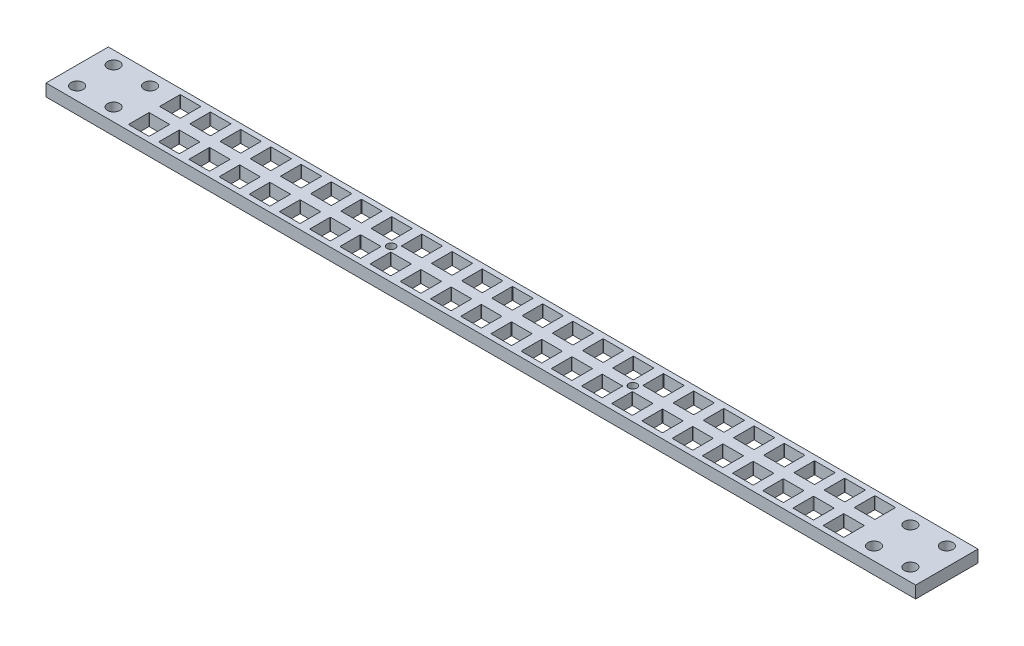
SolidWorks part; units mm, degrees
ref_plane "Front Plane" through (0, 0, 0) normal (0, 0, 1) x (1, 0, 0)
ref_plane "Top Plane" through (0, 0, 0) normal (0, 1, 0) x (1, 0, 0)
ref_plane "Right Plane" through (0, 0, 0) normal (1, 0, 0) x (0, 0, -1)
sketch "Sketch3" plane through (0, 0, 0) normal (0, 1, 0) x (1, 0, 0)
  line L0 (-49.8596, 35.1681) -> (-44.9596, 35.1681)
  line L1 (-57.4196, 42.8681) -> (119.2604, 42.8681) construction
  line L2 (-57.4196, 42.8681) -> (-57.4196, 30.0681) construction
  line L3 (-57.4196, 30.0681) -> (119.2604, 30.0681) construction
  line L4 (119.2604, 42.8681) -> (119.2604, 30.0681) construction
  line L5 (-57.4196, 42.8681) -> (119.2604, 30.0681) construction
  line L6 (-54.8696, 35.6681) -> (-54.8696, 32.6181) construction
  line L7 (-57.4196, 30.0681) -> (119.2604, 42.8681) construction
  line L8 (-57.2946, 35.0431) -> (-52.4446, 35.0431) construction
  line L9 (-57.2946, 35.0431) -> (-57.2946, 30.1931) construction
  line L10 (-57.2946, 30.1931) -> (-52.4446, 30.1931) construction
  line L11 (-52.4446, 35.0431) -> (-52.4446, 30.1931) construction
  line L12 (-57.2946, 35.0431) -> (-52.4446, 30.1931) construction
  line L13 (-57.2946, 30.1931) -> (-52.4446, 35.0431) construction
  line L14 (-57.3196, 35.1681) -> (-52.4196, 35.1681)
  line L15 (-57.4196, 35.0681) -> (-57.4196, 30.1681)
  line L16 (-57.3196, 30.0681) -> (-52.4196, 30.0681)
  line L17 (-52.3196, 35.0681) -> (-52.3196, 30.1681)
  line L18 (-57.4196, 35.1681) -> (-52.3196, 30.0681) construction
  line L19 (-57.4196, 30.0681) -> (-52.3196, 35.1681) construction
  line L20 (-49.9596, 35.0681) -> (-49.9596, 30.1681)
  line L21 (-49.8596, 30.0681) -> (-44.9596, 30.0681)
  line L22 (-44.8596, 35.0681) -> (-44.8596, 30.1681)
  line L24 (-47.4096, 35.6681) -> (-47.4096, 32.6181) construction
  line L25 (-49.8346, 35.0431) -> (-44.9846, 35.0431) construction
  line L26 (-49.8346, 35.0431) -> (-49.8346, 30.1931) construction
  line L27 (-49.8346, 30.1931) -> (-44.9846, 30.1931) construction
  line L28 (-44.9846, 35.0431) -> (-44.9846, 30.1931) construction
  line L29 (-49.8346, 35.0431) -> (-44.9846, 30.1931) construction
  line L30 (-49.8346, 30.1931) -> (-44.9846, 35.0431) construction
  line L31 (-49.9596, 35.1681) -> (-44.8596, 30.0681) construction
  line L32 (-49.9596, 30.0681) -> (-44.8596, 35.1681) construction
  line L33 (-42.3996, 35.1681) -> (-37.4996, 35.1681)
  line L34 (-42.4996, 35.0681) -> (-42.4996, 30.1681)
  line L35 (-42.3996, 30.0681) -> (-37.4996, 30.0681)
  line L36 (-37.3996, 35.0681) -> (-37.3996, 30.1681)
  line L37 (-76.4776, 44.1681) -> (138.3183, 44.1681)
  line L38 (-39.9496, 35.6681) -> (-39.9496, 32.6181) construction
  line L39 (-42.3746, 35.0431) -> (-37.5246, 35.0431) construction
  line L40 (-42.3746, 35.0431) -> (-42.3746, 30.1931) construction
  line L41 (-42.3746, 30.1931) -> (-37.5246, 30.1931) construction
  line L42 (-37.5246, 35.0431) -> (-37.5246, 30.1931) construction
  line L43 (-42.3746, 35.0431) -> (-37.5246, 30.1931) construction
  line L44 (-42.3746, 30.1931) -> (-37.5246, 35.0431) construction
  line L45 (-42.4996, 35.1681) -> (-37.3996, 30.0681) construction
  line L46 (-42.4996, 30.0681) -> (-37.3996, 35.1681) construction
  line L47 (-34.9396, 35.1681) -> (-30.0396, 35.1681)
  line L48 (-35.0396, 35.0681) -> (-35.0396, 30.1681)
  line L49 (-34.9396, 30.0681) -> (-30.0396, 30.0681)
  line L50 (-29.9396, 35.0681) -> (-29.9396, 30.1681)
  line L51 (-76.4776, 44.1681) -> (-76.4776, 28.7681)
  line L52 (-32.4896, 35.6681) -> (-32.4896, 32.6181) construction
  line L53 (-34.9146, 35.0431) -> (-30.0646, 35.0431) construction
  line L54 (-34.9146, 35.0431) -> (-34.9146, 30.1931) construction
  line L55 (-34.9146, 30.1931) -> (-30.0646, 30.1931) construction
  line L56 (-30.0646, 35.0431) -> (-30.0646, 30.1931) construction
  line L57 (-34.9146, 35.0431) -> (-30.0646, 30.1931) construction
  line L58 (-34.9146, 30.1931) -> (-30.0646, 35.0431) construction
  line L59 (-35.0396, 35.1681) -> (-29.9396, 30.0681) construction
  line L60 (-35.0396, 30.0681) -> (-29.9396, 35.1681) construction
  line L61 (-27.4796, 35.1681) -> (-22.5796, 35.1681)
  line L62 (-27.5796, 35.0681) -> (-27.5796, 30.1681)
  line L63 (-27.4796, 30.0681) -> (-22.5796, 30.0681)
  line L64 (-22.4796, 35.0681) -> (-22.4796, 30.1681)
  line L65 (-76.4776, 28.7681) -> (138.3183, 28.7681)
  line L66 (-25.0296, 35.6681) -> (-25.0296, 32.6181) construction
  line L67 (-27.4546, 35.0431) -> (-22.6046, 35.0431) construction
  line L68 (-27.4546, 35.0431) -> (-27.4546, 30.1931) construction
  line L69 (-27.4546, 30.1931) -> (-22.6046, 30.1931) construction
  line L70 (-22.6046, 35.0431) -> (-22.6046, 30.1931) construction
  line L71 (-27.4546, 35.0431) -> (-22.6046, 30.1931) construction
  line L72 (-27.4546, 30.1931) -> (-22.6046, 35.0431) construction
  line L73 (-27.5796, 35.1681) -> (-22.4796, 30.0681) construction
  line L74 (-27.5796, 30.0681) -> (-22.4796, 35.1681) construction
  line L75 (-20.0196, 35.1681) -> (-15.1196, 35.1681)
  line L76 (-20.1196, 35.0681) -> (-20.1196, 30.1681)
  line L77 (-20.0196, 30.0681) -> (-15.1196, 30.0681)
  line L78 (-15.0196, 35.0681) -> (-15.0196, 30.1681)
  line L79 (138.3183, 44.1681) -> (138.3183, 28.7681)
  line L80 (-17.5696, 35.6681) -> (-17.5696, 32.6181) construction
  line L81 (-19.9946, 35.0431) -> (-15.1446, 35.0431) construction
  line L82 (-19.9946, 35.0431) -> (-19.9946, 30.1931) construction
  line L83 (-19.9946, 30.1931) -> (-15.1446, 30.1931) construction
  line L84 (-15.1446, 35.0431) -> (-15.1446, 30.1931) construction
  line L85 (-19.9946, 35.0431) -> (-15.1446, 30.1931) construction
  line L86 (-19.9946, 30.1931) -> (-15.1446, 35.0431) construction
  line L87 (-20.1196, 35.1681) -> (-15.0196, 30.0681) construction
  line L88 (-20.1196, 30.0681) -> (-15.0196, 35.1681) construction
  line L89 (-12.5596, 35.1681) -> (-7.6596, 35.1681)
  line L90 (-12.6596, 35.0681) -> (-12.6596, 30.1681)
  line L91 (-12.5596, 30.0681) -> (-7.6596, 30.0681)
  line L92 (-7.5596, 35.0681) -> (-7.5596, 30.1681)
  line L93 (-76.4776, 44.1681) -> (138.3183, 28.7681) construction
  line L94 (-10.1096, 35.6681) -> (-10.1096, 32.6181) construction
  line L95 (-12.5346, 35.0431) -> (-7.6846, 35.0431) construction
  line L96 (-12.5346, 35.0431) -> (-12.5346, 30.1931) construction
  line L97 (-12.5346, 30.1931) -> (-7.6846, 30.1931) construction
  line L98 (-7.6846, 35.0431) -> (-7.6846, 30.1931) construction
  line L99 (-12.5346, 35.0431) -> (-7.6846, 30.1931) construction
  line L100 (-12.5346, 30.1931) -> (-7.6846, 35.0431) construction
  line L101 (-12.6596, 35.1681) -> (-7.5596, 30.0681) construction
  line L102 (-12.6596, 30.0681) -> (-7.5596, 35.1681) construction
  line L103 (-5.0996, 35.1681) -> (-0.1996, 35.1681)
  line L104 (-5.1996, 35.0681) -> (-5.1996, 30.1681)
  line L105 (-5.0996, 30.0681) -> (-0.1996, 30.0681)
  line L106 (-0.0996, 35.0681) -> (-0.0996, 30.1681)
  line L107 (-76.4776, 28.7681) -> (138.3183, 44.1681) construction
  line L108 (-2.6496, 35.6681) -> (-2.6496, 32.6181) construction
  line L109 (-5.0746, 35.0431) -> (-0.2246, 35.0431) construction
  line L110 (-5.0746, 35.0431) -> (-5.0746, 30.1931) construction
  line L111 (-5.0746, 30.1931) -> (-0.2246, 30.1931) construction
  line L112 (-0.2246, 35.0431) -> (-0.2246, 30.1931) construction
  line L113 (-5.0746, 35.0431) -> (-0.2246, 30.1931) construction
  line L114 (-5.0746, 30.1931) -> (-0.2246, 35.0431) construction
  line L115 (-5.1996, 35.1681) -> (-0.0996, 30.0681) construction
  line L116 (-5.1996, 30.0681) -> (-0.0996, 35.1681) construction
  line L117 (2.3604, 35.1681) -> (7.2604, 35.1681)
  line L118 (2.2604, 35.0681) -> (2.2604, 30.1681)
  line L119 (2.3604, 30.0681) -> (7.2604, 30.0681)
  line L120 (7.3604, 35.0681) -> (7.3604, 30.1681)
  line L122 (4.8104, 35.6681) -> (4.8104, 32.6181) construction
  line L123 (2.3854, 35.0431) -> (7.2354, 35.0431) construction
  line L124 (2.3854, 35.0431) -> (2.3854, 30.1931) construction
  line L125 (2.3854, 30.1931) -> (7.2354, 30.1931) construction
  line L126 (7.2354, 35.0431) -> (7.2354, 30.1931) construction
  line L127 (2.3854, 35.0431) -> (7.2354, 30.1931) construction
  line L128 (2.3854, 30.1931) -> (7.2354, 35.0431) construction
  line L129 (2.2604, 35.1681) -> (7.3604, 30.0681) construction
  line L130 (2.2604, 30.0681) -> (7.3604, 35.1681) construction
  line L131 (9.8204, 35.1681) -> (14.7204, 35.1681)
  line L132 (9.7204, 35.0681) -> (9.7204, 30.1681)
  line L133 (9.8204, 30.0681) -> (14.7204, 30.0681)
  line L134 (14.8204, 35.0681) -> (14.8204, 30.1681)
  line L136 (12.2704, 35.6681) -> (12.2704, 32.6181) construction
  line L137 (9.8454, 35.0431) -> (14.6954, 35.0431) construction
  line L138 (9.8454, 35.0431) -> (9.8454, 30.1931) construction
  line L139 (9.8454, 30.1931) -> (14.6954, 30.1931) construction
  line L140 (14.6954, 35.0431) -> (14.6954, 30.1931) construction
  line L141 (9.8454, 35.0431) -> (14.6954, 30.1931) construction
  line L142 (9.8454, 30.1931) -> (14.6954, 35.0431) construction
  line L143 (9.7204, 35.1681) -> (14.8204, 30.0681) construction
  line L144 (9.7204, 30.0681) -> (14.8204, 35.1681) construction
  line L145 (17.2804, 35.1681) -> (22.1804, 35.1681)
  line L146 (17.1804, 35.0681) -> (17.1804, 30.1681)
  line L147 (17.2804, 30.0681) -> (22.1804, 30.0681)
  line L148 (22.2804, 35.0681) -> (22.2804, 30.1681)
  line L150 (19.7304, 35.6681) -> (19.7304, 32.6181) construction
  line L151 (17.3054, 35.0431) -> (22.1554, 35.0431) construction
  line L152 (17.3054, 35.0431) -> (17.3054, 30.1931) construction
  line L153 (17.3054, 30.1931) -> (22.1554, 30.1931) construction
  line L154 (22.1554, 35.0431) -> (22.1554, 30.1931) construction
  line L155 (17.3054, 35.0431) -> (22.1554, 30.1931) construction
  line L156 (17.3054, 30.1931) -> (22.1554, 35.0431) construction
  line L157 (17.1804, 35.1681) -> (22.2804, 30.0681) construction
  line L158 (17.1804, 30.0681) -> (22.2804, 35.1681) construction
  line L159 (24.7404, 35.1681) -> (29.6404, 35.1681)
  line L160 (24.6404, 35.0681) -> (24.6404, 30.1681)
  line L161 (24.7404, 30.0681) -> (29.6404, 30.0681)
  line L162 (29.7404, 35.0681) -> (29.7404, 30.1681)
  line L164 (27.1904, 35.6681) -> (27.1904, 32.6181) construction
  line L165 (24.7654, 35.0431) -> (29.6154, 35.0431) construction
  line L166 (24.7654, 35.0431) -> (24.7654, 30.1931) construction
  line L167 (24.7654, 30.1931) -> (29.6154, 30.1931) construction
  line L168 (29.6154, 35.0431) -> (29.6154, 30.1931) construction
  line L169 (24.7654, 35.0431) -> (29.6154, 30.1931) construction
  line L170 (24.7654, 30.1931) -> (29.6154, 35.0431) construction
  line L171 (24.6404, 35.1681) -> (29.7404, 30.0681) construction
  line L172 (24.6404, 30.0681) -> (29.7404, 35.1681) construction
  line L173 (32.2004, 35.1681) -> (37.1004, 35.1681)
  line L174 (32.1004, 35.0681) -> (32.1004, 30.1681)
  line L175 (32.2004, 30.0681) -> (37.1004, 30.0681)
  line L176 (37.2004, 35.0681) -> (37.2004, 30.1681)
  line L178 (34.6504, 35.6681) -> (34.6504, 32.6181) construction
  line L179 (32.2254, 35.0431) -> (37.0754, 35.0431) construction
  line L180 (32.2254, 35.0431) -> (32.2254, 30.1931) construction
  line L181 (32.2254, 30.1931) -> (37.0754, 30.1931) construction
  line L182 (37.0754, 35.0431) -> (37.0754, 30.1931) construction
  line L183 (32.2254, 35.0431) -> (37.0754, 30.1931) construction
  line L184 (32.2254, 30.1931) -> (37.0754, 35.0431) construction
  line L185 (32.1004, 35.1681) -> (37.2004, 30.0681) construction
  line L186 (32.1004, 30.0681) -> (37.2004, 35.1681) construction
  line L187 (39.6604, 35.1681) -> (44.5604, 35.1681)
  line L188 (39.5604, 35.0681) -> (39.5604, 30.1681)
  line L189 (39.6604, 30.0681) -> (44.5604, 30.0681)
  line L190 (44.6604, 35.0681) -> (44.6604, 30.1681)
  line L192 (42.1104, 35.6681) -> (42.1104, 32.6181) construction
  line L193 (39.6854, 35.0431) -> (44.5354, 35.0431) construction
  line L194 (39.6854, 35.0431) -> (39.6854, 30.1931) construction
  line L195 (39.6854, 30.1931) -> (44.5354, 30.1931) construction
  line L196 (44.5354, 35.0431) -> (44.5354, 30.1931) construction
  line L197 (39.6854, 35.0431) -> (44.5354, 30.1931) construction
  line L198 (39.6854, 30.1931) -> (44.5354, 35.0431) construction
  line L199 (39.5604, 35.1681) -> (44.6604, 30.0681) construction
  line L200 (39.5604, 30.0681) -> (44.6604, 35.1681) construction
  line L201 (47.1204, 35.1681) -> (52.0204, 35.1681)
  line L202 (47.0204, 35.0681) -> (47.0204, 30.1681)
  line L203 (47.1204, 30.0681) -> (52.0204, 30.0681)
  line L204 (52.1204, 35.0681) -> (52.1204, 30.1681)
  line L206 (49.5704, 35.6681) -> (49.5704, 32.6181) construction
  line L207 (47.1454, 35.0431) -> (51.9954, 35.0431) construction
  line L208 (47.1454, 35.0431) -> (47.1454, 30.1931) construction
  line L209 (47.1454, 30.1931) -> (51.9954, 30.1931) construction
  line L210 (51.9954, 35.0431) -> (51.9954, 30.1931) construction
  line L211 (47.1454, 35.0431) -> (51.9954, 30.1931) construction
  line L212 (47.1454, 30.1931) -> (51.9954, 35.0431) construction
  line L213 (47.0204, 35.1681) -> (52.1204, 30.0681) construction
  line L214 (47.0204, 30.0681) -> (52.1204, 35.1681) construction
  line L215 (54.5804, 35.1681) -> (59.4804, 35.1681)
  line L216 (54.4804, 35.0681) -> (54.4804, 30.1681)
  line L217 (54.5804, 30.0681) -> (59.4804, 30.0681)
  line L218 (59.5804, 35.0681) -> (59.5804, 30.1681)
  line L220 (57.0304, 35.6681) -> (57.0304, 32.6181) construction
  line L221 (54.6054, 35.0431) -> (59.4554, 35.0431) construction
  line L222 (54.6054, 35.0431) -> (54.6054, 30.1931) construction
  line L223 (54.6054, 30.1931) -> (59.4554, 30.1931) construction
  line L224 (59.4554, 35.0431) -> (59.4554, 30.1931) construction
  line L225 (54.6054, 35.0431) -> (59.4554, 30.1931) construction
  line L226 (54.6054, 30.1931) -> (59.4554, 35.0431) construction
  line L227 (54.4804, 35.1681) -> (59.5804, 30.0681) construction
  line L228 (54.4804, 30.0681) -> (59.5804, 35.1681) construction
  line L229 (62.0404, 35.1681) -> (66.9404, 35.1681)
  line L230 (61.9404, 35.0681) -> (61.9404, 30.1681)
  line L231 (62.0404, 30.0681) -> (66.9404, 30.0681)
  line L232 (67.0404, 35.0681) -> (67.0404, 30.1681)
  line L234 (64.4904, 35.6681) -> (64.4904, 32.6181) construction
  line L235 (62.0654, 35.0431) -> (66.9154, 35.0431) construction
  line L236 (62.0654, 35.0431) -> (62.0654, 30.1931) construction
  line L237 (62.0654, 30.1931) -> (66.9154, 30.1931) construction
  line L238 (66.9154, 35.0431) -> (66.9154, 30.1931) construction
  line L239 (62.0654, 35.0431) -> (66.9154, 30.1931) construction
  line L240 (62.0654, 30.1931) -> (66.9154, 35.0431) construction
  line L241 (61.9404, 35.1681) -> (67.0404, 30.0681) construction
  line L242 (61.9404, 30.0681) -> (67.0404, 35.1681) construction
  line L243 (69.5004, 35.1681) -> (74.4004, 35.1681)
  line L244 (69.4004, 35.0681) -> (69.4004, 30.1681)
  line L245 (69.5004, 30.0681) -> (74.4004, 30.0681)
  line L246 (74.5004, 35.0681) -> (74.5004, 30.1681)
  line L248 (71.9504, 35.6681) -> (71.9504, 32.6181) construction
  line L249 (69.5254, 35.0431) -> (74.3754, 35.0431) construction
  line L250 (69.5254, 35.0431) -> (69.5254, 30.1931) construction
  line L251 (69.5254, 30.1931) -> (74.3754, 30.1931) construction
  line L252 (74.3754, 35.0431) -> (74.3754, 30.1931) construction
  line L253 (69.5254, 35.0431) -> (74.3754, 30.1931) construction
  line L254 (69.5254, 30.1931) -> (74.3754, 35.0431) construction
  line L255 (69.4004, 35.1681) -> (74.5004, 30.0681) construction
  line L256 (69.4004, 30.0681) -> (74.5004, 35.1681) construction
  line L257 (76.9604, 35.1681) -> (81.8604, 35.1681)
  line L258 (76.8604, 35.0681) -> (76.8604, 30.1681)
  line L259 (76.9604, 30.0681) -> (81.8604, 30.0681)
  line L260 (81.9604, 35.0681) -> (81.9604, 30.1681)
  line L262 (79.4104, 35.6681) -> (79.4104, 32.6181) construction
  line L263 (76.9854, 35.0431) -> (81.8354, 35.0431) construction
  line L264 (76.9854, 35.0431) -> (76.9854, 30.1931) construction
  line L265 (76.9854, 30.1931) -> (81.8354, 30.1931) construction
  line L266 (81.8354, 35.0431) -> (81.8354, 30.1931) construction
  line L267 (76.9854, 35.0431) -> (81.8354, 30.1931) construction
  line L268 (76.9854, 30.1931) -> (81.8354, 35.0431) construction
  line L269 (76.8604, 35.1681) -> (81.9604, 30.0681) construction
  line L270 (76.8604, 30.0681) -> (81.9604, 35.1681) construction
  line L271 (84.4204, 35.1681) -> (89.3204, 35.1681)
  line L272 (84.3204, 35.0681) -> (84.3204, 30.1681)
  line L273 (84.4204, 30.0681) -> (89.3204, 30.0681)
  line L274 (89.4204, 35.0681) -> (89.4204, 30.1681)
  line L276 (86.8704, 35.6681) -> (86.8704, 32.6181) construction
  line L277 (84.4454, 35.0431) -> (89.2954, 35.0431) construction
  line L278 (84.4454, 35.0431) -> (84.4454, 30.1931) construction
  line L279 (84.4454, 30.1931) -> (89.2954, 30.1931) construction
  line L280 (89.2954, 35.0431) -> (89.2954, 30.1931) construction
  line L281 (84.4454, 35.0431) -> (89.2954, 30.1931) construction
  line L282 (84.4454, 30.1931) -> (89.2954, 35.0431) construction
  line L283 (84.3204, 35.1681) -> (89.4204, 30.0681) construction
  line L284 (84.3204, 30.0681) -> (89.4204, 35.1681) construction
  line L285 (91.8804, 35.1681) -> (96.7804, 35.1681)
  line L286 (91.7804, 35.0681) -> (91.7804, 30.1681)
  line L287 (91.8804, 30.0681) -> (96.7804, 30.0681)
  line L288 (96.8804, 35.0681) -> (96.8804, 30.1681)
  line L290 (94.3304, 35.6681) -> (94.3304, 32.6181) construction
  line L291 (91.9054, 35.0431) -> (96.7554, 35.0431) construction
  line L292 (91.9054, 35.0431) -> (91.9054, 30.1931) construction
  line L293 (91.9054, 30.1931) -> (96.7554, 30.1931) construction
  line L294 (96.7554, 35.0431) -> (96.7554, 30.1931) construction
  line L305 (91.9054, 35.0431) -> (96.7554, 30.1931) construction
  line L306 (91.9054, 30.1931) -> (96.7554, 35.0431) construction
  line L307 (91.7804, 35.1681) -> (96.8804, 30.0681) construction
  line L308 (91.7804, 30.0681) -> (96.8804, 35.1681) construction
  line L309 (99.3404, 35.1681) -> (104.2404, 35.1681)
  line L310 (99.2404, 35.0681) -> (99.2404, 30.1681)
  line L311 (99.3404, 30.0681) -> (104.2404, 30.0681)
  line L312 (104.3404, 35.0681) -> (104.3404, 30.1681)
  line L314 (101.7904, 35.6681) -> (101.7904, 32.6181) construction
  line L315 (99.3654, 35.0431) -> (104.2154, 35.0431) construction
  line L316 (99.3654, 35.0431) -> (99.3654, 30.1931) construction
  line L317 (99.3654, 30.1931) -> (104.2154, 30.1931) construction
  line L318 (104.2154, 35.0431) -> (104.2154, 30.1931) construction
  line L319 (99.3654, 35.0431) -> (104.2154, 30.1931) construction
  line L320 (99.3654, 30.1931) -> (104.2154, 35.0431) construction
  line L321 (99.2404, 35.1681) -> (104.3404, 30.0681) construction
  line L322 (99.2404, 30.0681) -> (104.3404, 35.1681) construction
  line L323 (106.8004, 35.1681) -> (111.7004, 35.1681)
  line L324 (106.7004, 35.0681) -> (106.7004, 30.1681)
  line L325 (106.8004, 30.0681) -> (111.7004, 30.0681)
  line L326 (111.8004, 35.0681) -> (111.8004, 30.1681)
  line L328 (109.2504, 35.6681) -> (109.2504, 32.6181) construction
  line L329 (106.8254, 35.0431) -> (111.6754, 35.0431) construction
  line L330 (106.8254, 35.0431) -> (106.8254, 30.1931) construction
  line L331 (106.8254, 30.1931) -> (111.6754, 30.1931) construction
  line L332 (111.6754, 35.0431) -> (111.6754, 30.1931) construction
  line L333 (106.8254, 35.0431) -> (111.6754, 30.1931) construction
  line L334 (106.8254, 30.1931) -> (111.6754, 35.0431) construction
  line L335 (106.7004, 35.1681) -> (111.8004, 30.0681) construction
  line L336 (106.7004, 30.0681) -> (111.8004, 35.1681) construction
  line L337 (114.2604, 35.1681) -> (119.1604, 35.1681)
  line L338 (114.1604, 35.0681) -> (114.1604, 30.1681)
  line L339 (114.2604, 30.0681) -> (119.1604, 30.0681)
  line L340 (119.2604, 35.0681) -> (119.2604, 30.1681)
  line L342 (116.7104, 35.6681) -> (116.7104, 32.6181) construction
  line L343 (114.2854, 35.0431) -> (119.1354, 35.0431) construction
  line L344 (114.2854, 35.0431) -> (114.2854, 30.1931) construction
  line L345 (114.2854, 30.1931) -> (119.1354, 30.1931) construction
  line L346 (119.1354, 35.0431) -> (119.1354, 30.1931) construction
  line L347 (114.2854, 35.0431) -> (119.1354, 30.1931) construction
  line L348 (114.2854, 30.1931) -> (119.1354, 35.0431) construction
  line L349 (114.1604, 35.1681) -> (119.2604, 30.0681) construction
  line L350 (114.1604, 30.0681) -> (119.2604, 35.1681) construction
  line L351 (114.1604, 42.8681) -> (119.2604, 37.7681) construction
  line L352 (114.1604, 37.7681) -> (119.2604, 42.8681) construction
  line L353 (114.2854, 42.7431) -> (119.1354, 37.8931) construction
  line L354 (114.2854, 37.8931) -> (119.1354, 42.7431) construction
  line L355 (119.1354, 37.8931) -> (119.1354, 42.7431) construction
  line L356 (114.2854, 42.7431) -> (119.1354, 42.7431) construction
  line L357 (114.2854, 37.8931) -> (114.2854, 42.7431) construction
  line L358 (114.2854, 37.8931) -> (119.1354, 37.8931) construction
  line L359 (116.7104, 37.2681) -> (116.7104, 40.3181) construction
  line L360 (106.7004, 42.8681) -> (111.8004, 37.7681) construction
  line L361 (106.7004, 37.7681) -> (111.8004, 42.8681) construction
  line L362 (106.8254, 42.7431) -> (111.6754, 37.8931) construction
  line L363 (106.8254, 37.8931) -> (111.6754, 42.7431) construction
  line L364 (111.6754, 37.8931) -> (111.6754, 42.7431) construction
  line L365 (106.8254, 42.7431) -> (111.6754, 42.7431) construction
  line L366 (106.8254, 37.8931) -> (106.8254, 42.7431) construction
  line L367 (106.8254, 37.8931) -> (111.6754, 37.8931) construction
  line L368 (109.2504, 37.2681) -> (109.2504, 40.3181) construction
  line L369 (99.2404, 42.8681) -> (104.3404, 37.7681) construction
  line L370 (99.2404, 37.7681) -> (104.3404, 42.8681) construction
  line L371 (99.3654, 42.7431) -> (104.2154, 37.8931) construction
  line L372 (99.3654, 37.8931) -> (104.2154, 42.7431) construction
  line L373 (104.2154, 37.8931) -> (104.2154, 42.7431) construction
  line L374 (99.3654, 42.7431) -> (104.2154, 42.7431) construction
  line L375 (99.3654, 37.8931) -> (99.3654, 42.7431) construction
  line L376 (99.3654, 37.8931) -> (104.2154, 37.8931) construction
  line L377 (101.7904, 37.2681) -> (101.7904, 40.3181) construction
  line L378 (91.7804, 42.8681) -> (96.8804, 37.7681) construction
  line L379 (91.7804, 37.7681) -> (96.8804, 42.8681) construction
  line L380 (91.9054, 42.7431) -> (96.7554, 37.8931) construction
  line L381 (91.9054, 37.8931) -> (96.7554, 42.7431) construction
  line L383 (96.7554, 37.8931) -> (96.7554, 42.7431) construction
  line L384 (91.9054, 42.7431) -> (96.7554, 42.7431) construction
  line L385 (91.9054, 37.8931) -> (91.9054, 42.7431) construction
  line L386 (91.9054, 37.8931) -> (96.7554, 37.8931) construction
  line L387 (94.3304, 37.2681) -> (94.3304, 40.3181) construction
  line L388 (84.3204, 42.8681) -> (89.4204, 37.7681) construction
  line L389 (84.3204, 37.7681) -> (89.4204, 42.8681) construction
  line L390 (84.4454, 42.7431) -> (89.2954, 37.8931) construction
  line L391 (84.4454, 37.8931) -> (89.2954, 42.7431) construction
  line L392 (89.2954, 37.8931) -> (89.2954, 42.7431) construction
  line L393 (84.4454, 42.7431) -> (89.2954, 42.7431) construction
  line L394 (84.4454, 37.8931) -> (84.4454, 42.7431) construction
  line L395 (84.4454, 37.8931) -> (89.2954, 37.8931) construction
  line L396 (86.8704, 37.2681) -> (86.8704, 40.3181) construction
  line L397 (76.8604, 42.8681) -> (81.9604, 37.7681) construction
  line L398 (76.8604, 37.7681) -> (81.9604, 42.8681) construction
  line L399 (76.9854, 42.7431) -> (81.8354, 37.8931) construction
  line L400 (76.9854, 37.8931) -> (81.8354, 42.7431) construction
  line L401 (81.8354, 37.8931) -> (81.8354, 42.7431) construction
  line L402 (76.9854, 42.7431) -> (81.8354, 42.7431) construction
  line L403 (76.9854, 37.8931) -> (76.9854, 42.7431) construction
  line L404 (76.9854, 37.8931) -> (81.8354, 37.8931) construction
  line L405 (79.4104, 37.2681) -> (79.4104, 40.3181) construction
  line L406 (69.4004, 42.8681) -> (74.5004, 37.7681) construction
  line L407 (69.4004, 37.7681) -> (74.5004, 42.8681) construction
  line L408 (69.5254, 42.7431) -> (74.3754, 37.8931) construction
  line L409 (69.5254, 37.8931) -> (74.3754, 42.7431) construction
  line L410 (74.3754, 37.8931) -> (74.3754, 42.7431) construction
  line L411 (69.5254, 42.7431) -> (74.3754, 42.7431) construction
  line L412 (69.5254, 37.8931) -> (69.5254, 42.7431) construction
  line L413 (69.5254, 37.8931) -> (74.3754, 37.8931) construction
  line L414 (71.9504, 37.2681) -> (71.9504, 40.3181) construction
  line L415 (61.9404, 42.8681) -> (67.0404, 37.7681) construction
  line L416 (61.9404, 37.7681) -> (67.0404, 42.8681) construction
  line L417 (62.0654, 42.7431) -> (66.9154, 37.8931) construction
  line L418 (62.0654, 37.8931) -> (66.9154, 42.7431) construction
  line L419 (66.9154, 37.8931) -> (66.9154, 42.7431) construction
  line L420 (62.0654, 42.7431) -> (66.9154, 42.7431) construction
  line L421 (62.0654, 37.8931) -> (62.0654, 42.7431) construction
  line L422 (62.0654, 37.8931) -> (66.9154, 37.8931) construction
  line L423 (64.4904, 37.2681) -> (64.4904, 40.3181) construction
  line L424 (54.4804, 42.8681) -> (59.5804, 37.7681) construction
  line L425 (54.4804, 37.7681) -> (59.5804, 42.8681) construction
  line L426 (54.6054, 42.7431) -> (59.4554, 37.8931) construction
  line L427 (54.6054, 37.8931) -> (59.4554, 42.7431) construction
  line L428 (59.4554, 37.8931) -> (59.4554, 42.7431) construction
  line L429 (54.6054, 42.7431) -> (59.4554, 42.7431) construction
  line L430 (54.6054, 37.8931) -> (54.6054, 42.7431) construction
  line L431 (54.6054, 37.8931) -> (59.4554, 37.8931) construction
  line L432 (57.0304, 37.2681) -> (57.0304, 40.3181) construction
  line L433 (47.0204, 42.8681) -> (52.1204, 37.7681) construction
  line L434 (47.0204, 37.7681) -> (52.1204, 42.8681) construction
  line L435 (47.1454, 42.7431) -> (51.9954, 37.8931) construction
  line L436 (47.1454, 37.8931) -> (51.9954, 42.7431) construction
  line L437 (51.9954, 37.8931) -> (51.9954, 42.7431) construction
  line L438 (47.1454, 42.7431) -> (51.9954, 42.7431) construction
  line L439 (47.1454, 37.8931) -> (47.1454, 42.7431) construction
  line L440 (47.1454, 37.8931) -> (51.9954, 37.8931) construction
  line L441 (49.5704, 37.2681) -> (49.5704, 40.3181) construction
  line L442 (39.5604, 42.8681) -> (44.6604, 37.7681) construction
  line L443 (39.5604, 37.7681) -> (44.6604, 42.8681) construction
  line L444 (39.6854, 42.7431) -> (44.5354, 37.8931) construction
  line L445 (39.6854, 37.8931) -> (44.5354, 42.7431) construction
  line L446 (44.5354, 37.8931) -> (44.5354, 42.7431) construction
  line L447 (39.6854, 42.7431) -> (44.5354, 42.7431) construction
  line L448 (39.6854, 37.8931) -> (39.6854, 42.7431) construction
  line L449 (39.6854, 37.8931) -> (44.5354, 37.8931) construction
  line L450 (42.1104, 37.2681) -> (42.1104, 40.3181) construction
  line L451 (32.1004, 42.8681) -> (37.2004, 37.7681) construction
  line L452 (32.1004, 37.7681) -> (37.2004, 42.8681) construction
  line L453 (32.2254, 42.7431) -> (37.0754, 37.8931) construction
  line L454 (32.2254, 37.8931) -> (37.0754, 42.7431) construction
  line L455 (37.0754, 37.8931) -> (37.0754, 42.7431) construction
  line L456 (32.2254, 42.7431) -> (37.0754, 42.7431) construction
  line L457 (32.2254, 37.8931) -> (32.2254, 42.7431) construction
  line L458 (32.2254, 37.8931) -> (37.0754, 37.8931) construction
  line L459 (34.6504, 37.2681) -> (34.6504, 40.3181) construction
  line L460 (24.6404, 42.8681) -> (29.7404, 37.7681) construction
  line L461 (24.6404, 37.7681) -> (29.7404, 42.8681) construction
  line L462 (24.7654, 42.7431) -> (29.6154, 37.8931) construction
  line L463 (24.7654, 37.8931) -> (29.6154, 42.7431) construction
  line L464 (29.6154, 37.8931) -> (29.6154, 42.7431) construction
  line L465 (24.7654, 42.7431) -> (29.6154, 42.7431) construction
  line L466 (24.7654, 37.8931) -> (24.7654, 42.7431) construction
  line L467 (24.7654, 37.8931) -> (29.6154, 37.8931) construction
  line L468 (27.1904, 37.2681) -> (27.1904, 40.3181) construction
  line L469 (17.1804, 42.8681) -> (22.2804, 37.7681) construction
  line L470 (17.1804, 37.7681) -> (22.2804, 42.8681) construction
  line L471 (17.3054, 42.7431) -> (22.1554, 37.8931) construction
  line L472 (17.3054, 37.8931) -> (22.1554, 42.7431) construction
  line L473 (22.1554, 37.8931) -> (22.1554, 42.7431) construction
  line L474 (17.3054, 42.7431) -> (22.1554, 42.7431) construction
  line L475 (17.3054, 37.8931) -> (17.3054, 42.7431) construction
  line L476 (17.3054, 37.8931) -> (22.1554, 37.8931) construction
  line L477 (19.7304, 37.2681) -> (19.7304, 40.3181) construction
  line L478 (9.7204, 42.8681) -> (14.8204, 37.7681) construction
  line L479 (9.7204, 37.7681) -> (14.8204, 42.8681) construction
  line L480 (9.8454, 42.7431) -> (14.6954, 37.8931) construction
  line L481 (9.8454, 37.8931) -> (14.6954, 42.7431) construction
  line L482 (14.6954, 37.8931) -> (14.6954, 42.7431) construction
  line L483 (9.8454, 42.7431) -> (14.6954, 42.7431) construction
  line L484 (9.8454, 37.8931) -> (9.8454, 42.7431) construction
  line L485 (9.8454, 37.8931) -> (14.6954, 37.8931) construction
  line L486 (12.2704, 37.2681) -> (12.2704, 40.3181) construction
  line L487 (2.2604, 42.8681) -> (7.3604, 37.7681) construction
  line L488 (2.2604, 37.7681) -> (7.3604, 42.8681) construction
  line L489 (2.3854, 42.7431) -> (7.2354, 37.8931) construction
  line L490 (2.3854, 37.8931) -> (7.2354, 42.7431) construction
  line L491 (7.2354, 37.8931) -> (7.2354, 42.7431) construction
  line L492 (2.3854, 42.7431) -> (7.2354, 42.7431) construction
  line L493 (2.3854, 37.8931) -> (2.3854, 42.7431) construction
  line L494 (2.3854, 37.8931) -> (7.2354, 37.8931) construction
  line L495 (4.8104, 37.2681) -> (4.8104, 40.3181) construction
  line L496 (-5.1996, 42.8681) -> (-0.0996, 37.7681) construction
  line L497 (-5.1996, 37.7681) -> (-0.0996, 42.8681) construction
  line L508 (-5.0746, 42.7431) -> (-0.2246, 37.8931) construction
  line L509 (-5.0746, 37.8931) -> (-0.2246, 42.7431) construction
  line L510 (-0.2246, 37.8931) -> (-0.2246, 42.7431) construction
  line L511 (-5.0746, 42.7431) -> (-0.2246, 42.7431) construction
  line L512 (-5.0746, 37.8931) -> (-5.0746, 42.7431) construction
  line L513 (-5.0746, 37.8931) -> (-0.2246, 37.8931) construction
  line L514 (-2.6496, 37.2681) -> (-2.6496, 40.3181) construction
  line L515 (-12.6596, 42.8681) -> (-7.5596, 37.7681) construction
  line L516 (-12.6596, 37.7681) -> (-7.5596, 42.8681) construction
  line L517 (-12.5346, 42.7431) -> (-7.6846, 37.8931) construction
  line L518 (-12.5346, 37.8931) -> (-7.6846, 42.7431) construction
  line L519 (-7.6846, 37.8931) -> (-7.6846, 42.7431) construction
  line L520 (-12.5346, 42.7431) -> (-7.6846, 42.7431) construction
  line L521 (-12.5346, 37.8931) -> (-12.5346, 42.7431) construction
  line L522 (-12.5346, 37.8931) -> (-7.6846, 37.8931) construction
  line L523 (-10.1096, 37.2681) -> (-10.1096, 40.3181) construction
  line L524 (-20.1196, 42.8681) -> (-15.0196, 37.7681) construction
  line L525 (-20.1196, 37.7681) -> (-15.0196, 42.8681) construction
  line L526 (-19.9946, 42.7431) -> (-15.1446, 37.8931) construction
  line L527 (-19.9946, 37.8931) -> (-15.1446, 42.7431) construction
  line L528 (-15.1446, 37.8931) -> (-15.1446, 42.7431) construction
  line L529 (-19.9946, 42.7431) -> (-15.1446, 42.7431) construction
  line L530 (-19.9946, 37.8931) -> (-19.9946, 42.7431) construction
  line L531 (-19.9946, 37.8931) -> (-15.1446, 37.8931) construction
  line L532 (-17.5696, 37.2681) -> (-17.5696, 40.3181) construction
  line L533 (-27.5796, 42.8681) -> (-22.4796, 37.7681) construction
  line L534 (-27.5796, 37.7681) -> (-22.4796, 42.8681) construction
  line L535 (-27.4546, 42.7431) -> (-22.6046, 37.8931) construction
  line L536 (-27.4546, 37.8931) -> (-22.6046, 42.7431) construction
  line L537 (-22.6046, 37.8931) -> (-22.6046, 42.7431) construction
  line L538 (-27.4546, 42.7431) -> (-22.6046, 42.7431) construction
  line L539 (-27.4546, 37.8931) -> (-27.4546, 42.7431) construction
  line L540 (-27.4546, 37.8931) -> (-22.6046, 37.8931) construction
  line L541 (-25.0296, 37.2681) -> (-25.0296, 40.3181) construction
  line L542 (-35.0396, 42.8681) -> (-29.9396, 37.7681) construction
  line L543 (-35.0396, 37.7681) -> (-29.9396, 42.8681) construction
  line L544 (-34.9146, 42.7431) -> (-30.0646, 37.8931) construction
  line L545 (-34.9146, 37.8931) -> (-30.0646, 42.7431) construction
  line L546 (-30.0646, 37.8931) -> (-30.0646, 42.7431) construction
  line L547 (-34.9146, 42.7431) -> (-30.0646, 42.7431) construction
  line L548 (-34.9146, 37.8931) -> (-34.9146, 42.7431) construction
  line L549 (-34.9146, 37.8931) -> (-30.0646, 37.8931) construction
  line L550 (-32.4896, 37.2681) -> (-32.4896, 40.3181) construction
  line L551 (-42.4996, 42.8681) -> (-37.3996, 37.7681) construction
  line L552 (-42.4996, 37.7681) -> (-37.3996, 42.8681) construction
  line L553 (-42.3746, 42.7431) -> (-37.5246, 37.8931) construction
  line L554 (-42.3746, 37.8931) -> (-37.5246, 42.7431) construction
  line L555 (-37.5246, 37.8931) -> (-37.5246, 42.7431) construction
  line L556 (-42.3746, 42.7431) -> (-37.5246, 42.7431) construction
  line L557 (-42.3746, 37.8931) -> (-42.3746, 42.7431) construction
  line L558 (-42.3746, 37.8931) -> (-37.5246, 37.8931) construction
  line L559 (-39.9496, 37.2681) -> (-39.9496, 40.3181) construction
  line L560 (-49.9596, 42.8681) -> (-44.8596, 37.7681) construction
  line L561 (-49.9596, 37.7681) -> (-44.8596, 42.8681) construction
  line L562 (-49.8346, 42.7431) -> (-44.9846, 37.8931) construction
  line L563 (-49.8346, 37.8931) -> (-44.9846, 42.7431) construction
  line L564 (-44.9846, 37.8931) -> (-44.9846, 42.7431) construction
  line L565 (-49.8346, 42.7431) -> (-44.9846, 42.7431) construction
  line L566 (-49.8346, 37.8931) -> (-49.8346, 42.7431) construction
  line L567 (-49.8346, 37.8931) -> (-44.9846, 37.8931) construction
  line L568 (-47.4096, 37.2681) -> (-47.4096, 40.3181) construction
  line L569 (-57.4196, 42.8681) -> (-52.3196, 37.7681) construction
  line L570 (-57.4196, 37.7681) -> (-52.3196, 42.8681) construction
  line L571 (-57.2946, 42.7431) -> (-52.4446, 37.8931) construction
  line L572 (-57.2946, 37.8931) -> (-52.4446, 42.7431) construction
  line L573 (-52.4446, 37.8931) -> (-52.4446, 42.7431) construction
  line L574 (-57.2946, 42.7431) -> (-52.4446, 42.7431) construction
  line L575 (-57.2946, 37.8931) -> (-57.2946, 42.7431) construction
  line L576 (-57.2946, 37.8931) -> (-52.4446, 37.8931) construction
  line L577 (-54.8696, 37.7681) -> (-54.8696, 40.3181) construction
  line L578 (119.2604, 37.8681) -> (119.2604, 42.7681)
  line L579 (114.2604, 42.8681) -> (119.1604, 42.8681)
  line L580 (114.1604, 37.8681) -> (114.1604, 42.7681)
  line L581 (114.2604, 37.7681) -> (119.1604, 37.7681)
  line L582 (111.8004, 37.8681) -> (111.8004, 42.7681)
  line L583 (106.8004, 42.8681) -> (111.7004, 42.8681)
  line L584 (106.7004, 37.8681) -> (106.7004, 42.7681)
  line L585 (106.8004, 37.7681) -> (111.7004, 37.7681)
  line L586 (104.3404, 37.8681) -> (104.3404, 42.7681)
  line L587 (99.3404, 42.8681) -> (104.2404, 42.8681)
  line L588 (99.2404, 37.8681) -> (99.2404, 42.7681)
  line L589 (99.3404, 37.7681) -> (104.2404, 37.7681)
  line L590 (96.8804, 37.8681) -> (96.8804, 42.7681)
  line L591 (91.8804, 42.8681) -> (96.7804, 42.8681)
  line L592 (91.7804, 37.8681) -> (91.7804, 42.7681)
  line L593 (91.8804, 37.7681) -> (96.7804, 37.7681)
  line L594 (89.4204, 37.8681) -> (89.4204, 42.7681)
  line L595 (84.4204, 42.8681) -> (89.3204, 42.8681)
  line L596 (84.3204, 37.8681) -> (84.3204, 42.7681)
  line L597 (84.4204, 37.7681) -> (89.3204, 37.7681)
  line L598 (81.9604, 37.8681) -> (81.9604, 42.7681)
  line L599 (76.9604, 42.8681) -> (81.8604, 42.8681)
  line L600 (76.8604, 37.8681) -> (76.8604, 42.7681)
  line L601 (76.9604, 37.7681) -> (81.8604, 37.7681)
  line L602 (74.5004, 37.8681) -> (74.5004, 42.7681)
  line L603 (69.5004, 42.8681) -> (74.4004, 42.8681)
  line L616 (69.4004, 37.8681) -> (69.4004, 42.7681)
  line L617 (69.5004, 37.7681) -> (74.4004, 37.7681)
  line L618 (67.0404, 37.8681) -> (67.0404, 42.7681)
  line L619 (62.0404, 42.8681) -> (66.9404, 42.8681)
  line L620 (61.9404, 37.8681) -> (61.9404, 42.7681)
  line L621 (62.0404, 37.7681) -> (66.9404, 37.7681)
  line L622 (59.5804, 37.8681) -> (59.5804, 42.7681)
  line L623 (54.5804, 42.8681) -> (59.4804, 42.8681)
  line L624 (54.4804, 37.8681) -> (54.4804, 42.7681)
  line L625 (54.5804, 37.7681) -> (59.4804, 37.7681)
  line L626 (52.1204, 37.8681) -> (52.1204, 42.7681)
  line L627 (47.1204, 42.8681) -> (52.0204, 42.8681)
  line L628 (47.0204, 37.8681) -> (47.0204, 42.7681)
  line L629 (47.1204, 37.7681) -> (52.0204, 37.7681)
  line L630 (44.6604, 37.8681) -> (44.6604, 42.7681)
  line L631 (39.6604, 42.8681) -> (44.5604, 42.8681)
  line L632 (39.5604, 37.8681) -> (39.5604, 42.7681)
  line L633 (39.6604, 37.7681) -> (44.5604, 37.7681)
  line L634 (37.2004, 37.8681) -> (37.2004, 42.7681)
  line L635 (32.2004, 42.8681) -> (37.1004, 42.8681)
  line L636 (32.1004, 37.8681) -> (32.1004, 42.7681)
  line L637 (32.2004, 37.7681) -> (37.1004, 37.7681)
  line L638 (29.7404, 37.8681) -> (29.7404, 42.7681)
  line L639 (24.7404, 42.8681) -> (29.6404, 42.8681)
  line L640 (24.6404, 37.8681) -> (24.6404, 42.7681)
  line L641 (24.7404, 37.7681) -> (29.6404, 37.7681)
  line L642 (22.2804, 37.8681) -> (22.2804, 42.7681)
  line L643 (17.2804, 42.8681) -> (22.1804, 42.8681)
  line L644 (17.1804, 37.8681) -> (17.1804, 42.7681)
  line L645 (17.2804, 37.7681) -> (22.1804, 37.7681)
  line L646 (14.8204, 37.8681) -> (14.8204, 42.7681)
  line L647 (9.8204, 42.8681) -> (14.7204, 42.8681)
  line L648 (9.7204, 37.8681) -> (9.7204, 42.7681)
  line L649 (9.8204, 37.7681) -> (14.7204, 37.7681)
  line L650 (7.3604, 37.8681) -> (7.3604, 42.7681)
  line L651 (2.3604, 42.8681) -> (7.2604, 42.8681)
  line L652 (2.2604, 37.8681) -> (2.2604, 42.7681)
  line L653 (2.3604, 37.7681) -> (7.2604, 37.7681)
  line L654 (-0.0996, 37.8681) -> (-0.0996, 42.7681)
  line L655 (-5.0996, 42.8681) -> (-0.1996, 42.8681)
  line L656 (-5.1996, 37.8681) -> (-5.1996, 42.7681)
  line L657 (-5.0996, 37.7681) -> (-0.1996, 37.7681)
  line L658 (-7.5596, 37.8681) -> (-7.5596, 42.7681)
  line L659 (-12.5596, 42.8681) -> (-7.6596, 42.8681)
  line L660 (-12.6596, 37.8681) -> (-12.6596, 42.7681)
  line L661 (-12.5596, 37.7681) -> (-7.6596, 37.7681)
  line L662 (-15.0196, 37.8681) -> (-15.0196, 42.7681)
  line L663 (-20.0196, 42.8681) -> (-15.1196, 42.8681)
  line L664 (-20.1196, 37.8681) -> (-20.1196, 42.7681)
  line L665 (-20.0196, 37.7681) -> (-15.1196, 37.7681)
  line L666 (-22.4796, 37.8681) -> (-22.4796, 42.7681)
  line L667 (-27.4796, 42.8681) -> (-22.5796, 42.8681)
  line L668 (-27.5796, 37.8681) -> (-27.5796, 42.7681)
  line L669 (-27.4796, 37.7681) -> (-22.5796, 37.7681)
  line L670 (-29.9396, 37.8681) -> (-29.9396, 42.7681)
  line L671 (-34.9396, 42.8681) -> (-30.0396, 42.8681)
  line L672 (-35.0396, 37.8681) -> (-35.0396, 42.7681)
  line L673 (-34.9396, 37.7681) -> (-30.0396, 37.7681)
  line L674 (-37.3996, 37.8681) -> (-37.3996, 42.7681)
  line L675 (-42.3996, 42.8681) -> (-37.4996, 42.8681)
  line L676 (-42.4996, 37.8681) -> (-42.4996, 42.7681)
  line L677 (-42.3996, 37.7681) -> (-37.4996, 37.7681)
  line L678 (-44.8596, 37.8681) -> (-44.8596, 42.7681)
  line L679 (-49.8596, 42.8681) -> (-44.9596, 42.8681)
  line L680 (-49.9596, 37.8681) -> (-49.9596, 42.7681)
  line L681 (-52.3196, 37.8681) -> (-52.3196, 42.7681)
  line L682 (-57.3196, 42.8681) -> (-52.4196, 42.8681)
  line L683 (-57.4196, 37.8681) -> (-57.4196, 42.7681)
  line L684 (-57.3196, 37.7681) -> (-52.4196, 37.7681)
  line L685 (-49.8596, 37.7681) -> (-44.9596, 37.7681)
  line L686 (-49.8596, 35.1681) -> (-44.9596, 35.1681) [skipped]
  arc A8 (-52.4196, 30.0681) -> (-52.3196, 30.1681) centre (-52.4196, 30.1681) ccw
  arc A9 (-52.3196, 35.0681) -> (-52.4196, 35.1681) centre (-52.4196, 35.0681) ccw
  arc A10 (-57.3196, 35.1681) -> (-57.4196, 35.0681) centre (-57.3196, 35.0681) ccw
  arc A11 (-57.4196, 30.1681) -> (-57.3196, 30.0681) centre (-57.3196, 30.1681) ccw
  arc A12 (-44.9596, 30.0681) -> (-44.8596, 30.1681) centre (-44.9596, 30.1681) ccw
  arc A13 (-44.8596, 35.0681) -> (-44.9596, 35.1681) centre (-44.9596, 35.0681) ccw
  arc A14 (-49.8596, 35.1681) -> (-49.9596, 35.0681) centre (-49.8596, 35.0681) ccw
  arc A15 (-49.9596, 30.1681) -> (-49.8596, 30.0681) centre (-49.8596, 30.1681) ccw
  arc A16 (-37.4996, 30.0681) -> (-37.3996, 30.1681) centre (-37.4996, 30.1681) ccw
  arc A17 (-37.3996, 35.0681) -> (-37.4996, 35.1681) centre (-37.4996, 35.0681) ccw
  arc A18 (-42.3996, 35.1681) -> (-42.4996, 35.0681) centre (-42.3996, 35.0681) ccw
  arc A19 (-42.4996, 30.1681) -> (-42.3996, 30.0681) centre (-42.3996, 30.1681) ccw
  arc A20 (-30.0396, 30.0681) -> (-29.9396, 30.1681) centre (-30.0396, 30.1681) ccw
  arc A21 (-29.9396, 35.0681) -> (-30.0396, 35.1681) centre (-30.0396, 35.0681) ccw
  arc A22 (-34.9396, 35.1681) -> (-35.0396, 35.0681) centre (-34.9396, 35.0681) ccw
  arc A23 (-35.0396, 30.1681) -> (-34.9396, 30.0681) centre (-34.9396, 30.1681) ccw
  arc A24 (-22.5796, 30.0681) -> (-22.4796, 30.1681) centre (-22.5796, 30.1681) ccw
  arc A25 (-22.4796, 35.0681) -> (-22.5796, 35.1681) centre (-22.5796, 35.0681) ccw
  arc A26 (-27.4796, 35.1681) -> (-27.5796, 35.0681) centre (-27.4796, 35.0681) ccw
  arc A27 (-27.5796, 30.1681) -> (-27.4796, 30.0681) centre (-27.4796, 30.1681) ccw
  arc A28 (-15.1196, 30.0681) -> (-15.0196, 30.1681) centre (-15.1196, 30.1681) ccw
  arc A29 (-15.0196, 35.0681) -> (-15.1196, 35.1681) centre (-15.1196, 35.0681) ccw
  arc A30 (-20.0196, 35.1681) -> (-20.1196, 35.0681) centre (-20.0196, 35.0681) ccw
  arc A31 (-20.1196, 30.1681) -> (-20.0196, 30.0681) centre (-20.0196, 30.1681) ccw
  arc A32 (-7.6596, 30.0681) -> (-7.5596, 30.1681) centre (-7.6596, 30.1681) ccw
  arc A33 (-7.5596, 35.0681) -> (-7.6596, 35.1681) centre (-7.6596, 35.0681) ccw
  arc A34 (-12.5596, 35.1681) -> (-12.6596, 35.0681) centre (-12.5596, 35.0681) ccw
  arc A35 (-12.6596, 30.1681) -> (-12.5596, 30.0681) centre (-12.5596, 30.1681) ccw
  arc A36 (-0.1996, 30.0681) -> (-0.0996, 30.1681) centre (-0.1996, 30.1681) ccw
  arc A37 (-0.0996, 35.0681) -> (-0.1996, 35.1681) centre (-0.1996, 35.0681) ccw
  arc A38 (-5.0996, 35.1681) -> (-5.1996, 35.0681) centre (-5.0996, 35.0681) ccw
  arc A39 (-5.1996, 30.1681) -> (-5.0996, 30.0681) centre (-5.0996, 30.1681) ccw
  arc A40 (7.2604, 30.0681) -> (7.3604, 30.1681) centre (7.2604, 30.1681) ccw
  arc A41 (7.3604, 35.0681) -> (7.2604, 35.1681) centre (7.2604, 35.0681) ccw
  arc A42 (2.3604, 35.1681) -> (2.2604, 35.0681) centre (2.3604, 35.0681) ccw
  arc A43 (2.2604, 30.1681) -> (2.3604, 30.0681) centre (2.3604, 30.1681) ccw
  arc A44 (14.7204, 30.0681) -> (14.8204, 30.1681) centre (14.7204, 30.1681) ccw
  arc A45 (14.8204, 35.0681) -> (14.7204, 35.1681) centre (14.7204, 35.0681) ccw
  arc A46 (9.8204, 35.1681) -> (9.7204, 35.0681) centre (9.8204, 35.0681) ccw
  arc A47 (9.7204, 30.1681) -> (9.8204, 30.0681) centre (9.8204, 30.1681) ccw
  arc A48 (22.1804, 30.0681) -> (22.2804, 30.1681) centre (22.1804, 30.1681) ccw
  arc A49 (22.2804, 35.0681) -> (22.1804, 35.1681) centre (22.1804, 35.0681) ccw
  arc A50 (17.2804, 35.1681) -> (17.1804, 35.0681) centre (17.2804, 35.0681) ccw
  arc A51 (17.1804, 30.1681) -> (17.2804, 30.0681) centre (17.2804, 30.1681) ccw
  arc A52 (29.6404, 30.0681) -> (29.7404, 30.1681) centre (29.6404, 30.1681) ccw
  arc A53 (29.7404, 35.0681) -> (29.6404, 35.1681) centre (29.6404, 35.0681) ccw
  arc A54 (24.7404, 35.1681) -> (24.6404, 35.0681) centre (24.7404, 35.0681) ccw
  arc A55 (24.6404, 30.1681) -> (24.7404, 30.0681) centre (24.7404, 30.1681) ccw
  arc A56 (37.1004, 30.0681) -> (37.2004, 30.1681) centre (37.1004, 30.1681) ccw
  arc A57 (37.2004, 35.0681) -> (37.1004, 35.1681) centre (37.1004, 35.0681) ccw
  arc A58 (32.2004, 35.1681) -> (32.1004, 35.0681) centre (32.2004, 35.0681) ccw
  arc A59 (32.1004, 30.1681) -> (32.2004, 30.0681) centre (32.2004, 30.1681) ccw
  arc A60 (44.5604, 30.0681) -> (44.6604, 30.1681) centre (44.5604, 30.1681) ccw
  arc A61 (44.6604, 35.0681) -> (44.5604, 35.1681) centre (44.5604, 35.0681) ccw
  arc A62 (39.6604, 35.1681) -> (39.5604, 35.0681) centre (39.6604, 35.0681) ccw
  arc A63 (39.5604, 30.1681) -> (39.6604, 30.0681) centre (39.6604, 30.1681) ccw
  arc A64 (52.0204, 30.0681) -> (52.1204, 30.1681) centre (52.0204, 30.1681) ccw
  arc A65 (52.1204, 35.0681) -> (52.0204, 35.1681) centre (52.0204, 35.0681) ccw
  arc A66 (47.1204, 35.1681) -> (47.0204, 35.0681) centre (47.1204, 35.0681) ccw
  arc A67 (47.0204, 30.1681) -> (47.1204, 30.0681) centre (47.1204, 30.1681) ccw
  arc A68 (59.4804, 30.0681) -> (59.5804, 30.1681) centre (59.4804, 30.1681) ccw
  arc A69 (59.5804, 35.0681) -> (59.4804, 35.1681) centre (59.4804, 35.0681) ccw
  arc A70 (54.5804, 35.1681) -> (54.4804, 35.0681) centre (54.5804, 35.0681) ccw
  arc A71 (54.4804, 30.1681) -> (54.5804, 30.0681) centre (54.5804, 30.1681) ccw
  arc A72 (66.9404, 30.0681) -> (67.0404, 30.1681) centre (66.9404, 30.1681) ccw
  arc A73 (67.0404, 35.0681) -> (66.9404, 35.1681) centre (66.9404, 35.0681) ccw
  arc A74 (62.0404, 35.1681) -> (61.9404, 35.0681) centre (62.0404, 35.0681) ccw
  arc A75 (61.9404, 30.1681) -> (62.0404, 30.0681) centre (62.0404, 30.1681) ccw
  arc A76 (74.4004, 30.0681) -> (74.5004, 30.1681) centre (74.4004, 30.1681) ccw
  arc A77 (74.5004, 35.0681) -> (74.4004, 35.1681) centre (74.4004, 35.0681) ccw
  arc A78 (69.5004, 35.1681) -> (69.4004, 35.0681) centre (69.5004, 35.0681) ccw
  arc A79 (69.4004, 30.1681) -> (69.5004, 30.0681) centre (69.5004, 30.1681) ccw
  arc A80 (81.8604, 30.0681) -> (81.9604, 30.1681) centre (81.8604, 30.1681) ccw
  arc A81 (81.9604, 35.0681) -> (81.8604, 35.1681) centre (81.8604, 35.0681) ccw
  arc A82 (76.9604, 35.1681) -> (76.8604, 35.0681) centre (76.9604, 35.0681) ccw
  arc A83 (76.8604, 30.1681) -> (76.9604, 30.0681) centre (76.9604, 30.1681) ccw
  arc A84 (89.3204, 30.0681) -> (89.4204, 30.1681) centre (89.3204, 30.1681) ccw
  arc A85 (89.4204, 35.0681) -> (89.3204, 35.1681) centre (89.3204, 35.0681) ccw
  arc A86 (84.4204, 35.1681) -> (84.3204, 35.0681) centre (84.4204, 35.0681) ccw
  arc A87 (84.3204, 30.1681) -> (84.4204, 30.0681) centre (84.4204, 30.1681) ccw
  arc A88 (96.7804, 30.0681) -> (96.8804, 30.1681) centre (96.7804, 30.1681) ccw
  arc A89 (96.8804, 35.0681) -> (96.7804, 35.1681) centre (96.7804, 35.0681) ccw
  arc A90 (91.8804, 35.1681) -> (91.7804, 35.0681) centre (91.8804, 35.0681) ccw
  arc A91 (91.7804, 30.1681) -> (91.8804, 30.0681) centre (91.8804, 30.1681) ccw
  arc A92 (104.2404, 30.0681) -> (104.3404, 30.1681) centre (104.2404, 30.1681) ccw
  arc A93 (104.3404, 35.0681) -> (104.2404, 35.1681) centre (104.2404, 35.0681) ccw
  arc A94 (99.3404, 35.1681) -> (99.2404, 35.0681) centre (99.3404, 35.0681) ccw
  arc A95 (99.2404, 30.1681) -> (99.3404, 30.0681) centre (99.3404, 30.1681) ccw
  arc A96 (111.7004, 30.0681) -> (111.8004, 30.1681) centre (111.7004, 30.1681) ccw
  arc A97 (111.8004, 35.0681) -> (111.7004, 35.1681) centre (111.7004, 35.0681) ccw
  arc A98 (106.8004, 35.1681) -> (106.7004, 35.0681) centre (106.8004, 35.0681) ccw
  arc A99 (106.7004, 30.1681) -> (106.8004, 30.0681) centre (106.8004, 30.1681) ccw
  arc A100 (119.1604, 30.0681) -> (119.2604, 30.1681) centre (119.1604, 30.1681) ccw
  arc A101 (119.2604, 35.0681) -> (119.1604, 35.1681) centre (119.1604, 35.0681) ccw
  arc A102 (114.2604, 35.1681) -> (114.1604, 35.0681) centre (114.2604, 35.0681) ccw
  arc A103 (114.1604, 30.1681) -> (114.2604, 30.0681) centre (114.2604, 30.1681) ccw
  arc A104 (114.1604, 42.7681) -> (114.2604, 42.8681) centre (114.2604, 42.7681) cw
  arc A105 (114.2604, 37.7681) -> (114.1604, 37.8681) centre (114.2604, 37.8681) cw
  arc A106 (119.2604, 37.8681) -> (119.1604, 37.7681) centre (119.1604, 37.8681) cw
  arc A107 (119.1604, 42.8681) -> (119.2604, 42.7681) centre (119.1604, 42.7681) cw
  arc A108 (106.7004, 42.7681) -> (106.8004, 42.8681) centre (106.8004, 42.7681) cw
  arc A109 (106.8004, 37.7681) -> (106.7004, 37.8681) centre (106.8004, 37.8681) cw
  arc A110 (111.8004, 37.8681) -> (111.7004, 37.7681) centre (111.7004, 37.8681) cw
  arc A111 (111.7004, 42.8681) -> (111.8004, 42.7681) centre (111.7004, 42.7681) cw
  arc A112 (99.2404, 42.7681) -> (99.3404, 42.8681) centre (99.3404, 42.7681) cw
  arc A113 (99.3404, 37.7681) -> (99.2404, 37.8681) centre (99.3404, 37.8681) cw
  arc A114 (104.3404, 37.8681) -> (104.2404, 37.7681) centre (104.2404, 37.8681) cw
  arc A115 (104.2404, 42.8681) -> (104.3404, 42.7681) centre (104.2404, 42.7681) cw
  arc A116 (91.7804, 42.7681) -> (91.8804, 42.8681) centre (91.8804, 42.7681) cw
  arc A117 (91.8804, 37.7681) -> (91.7804, 37.8681) centre (91.8804, 37.8681) cw
  arc A118 (96.8804, 37.8681) -> (96.7804, 37.7681) centre (96.7804, 37.8681) cw
  arc A119 (96.7804, 42.8681) -> (96.8804, 42.7681) centre (96.7804, 42.7681) cw
  arc A120 (84.3204, 42.7681) -> (84.4204, 42.8681) centre (84.4204, 42.7681) cw
  arc A121 (84.4204, 37.7681) -> (84.3204, 37.8681) centre (84.4204, 37.8681) cw
  arc A122 (89.4204, 37.8681) -> (89.3204, 37.7681) centre (89.3204, 37.8681) cw
  arc A123 (89.3204, 42.8681) -> (89.4204, 42.7681) centre (89.3204, 42.7681) cw
  arc A124 (76.8604, 42.7681) -> (76.9604, 42.8681) centre (76.9604, 42.7681) cw
  arc A125 (76.9604, 37.7681) -> (76.8604, 37.8681) centre (76.9604, 37.8681) cw
  arc A126 (81.9604, 37.8681) -> (81.8604, 37.7681) centre (81.8604, 37.8681) cw
  arc A127 (81.8604, 42.8681) -> (81.9604, 42.7681) centre (81.8604, 42.7681) cw
  arc A128 (69.4004, 42.7681) -> (69.5004, 42.8681) centre (69.5004, 42.7681) cw
  arc A129 (69.5004, 37.7681) -> (69.4004, 37.8681) centre (69.5004, 37.8681) cw
  arc A130 (74.5004, 37.8681) -> (74.4004, 37.7681) centre (74.4004, 37.8681) cw
  arc A131 (74.4004, 42.8681) -> (74.5004, 42.7681) centre (74.4004, 42.7681) cw
  arc A132 (61.9404, 42.7681) -> (62.0404, 42.8681) centre (62.0404, 42.7681) cw
  arc A133 (62.0404, 37.7681) -> (61.9404, 37.8681) centre (62.0404, 37.8681) cw
  arc A134 (67.0404, 37.8681) -> (66.9404, 37.7681) centre (66.9404, 37.8681) cw
  arc A135 (66.9404, 42.8681) -> (67.0404, 42.7681) centre (66.9404, 42.7681) cw
  arc A136 (54.4804, 42.7681) -> (54.5804, 42.8681) centre (54.5804, 42.7681) cw
  arc A137 (54.5804, 37.7681) -> (54.4804, 37.8681) centre (54.5804, 37.8681) cw
  arc A138 (59.5804, 37.8681) -> (59.4804, 37.7681) centre (59.4804, 37.8681) cw
  arc A139 (59.4804, 42.8681) -> (59.5804, 42.7681) centre (59.4804, 42.7681) cw
  arc A140 (47.0204, 42.7681) -> (47.1204, 42.8681) centre (47.1204, 42.7681) cw
  arc A141 (47.1204, 37.7681) -> (47.0204, 37.8681) centre (47.1204, 37.8681) cw
  arc A142 (52.1204, 37.8681) -> (52.0204, 37.7681) centre (52.0204, 37.8681) cw
  arc A143 (52.0204, 42.8681) -> (52.1204, 42.7681) centre (52.0204, 42.7681) cw
  arc A144 (39.5604, 42.7681) -> (39.6604, 42.8681) centre (39.6604, 42.7681) cw
  arc A145 (39.6604, 37.7681) -> (39.5604, 37.8681) centre (39.6604, 37.8681) cw
  arc A146 (44.6604, 37.8681) -> (44.5604, 37.7681) centre (44.5604, 37.8681) cw
  arc A147 (44.5604, 42.8681) -> (44.6604, 42.7681) centre (44.5604, 42.7681) cw
  arc A148 (32.1004, 42.7681) -> (32.2004, 42.8681) centre (32.2004, 42.7681) cw
  arc A149 (32.2004, 37.7681) -> (32.1004, 37.8681) centre (32.2004, 37.8681) cw
  arc A150 (37.2004, 37.8681) -> (37.1004, 37.7681) centre (37.1004, 37.8681) cw
  arc A151 (37.1004, 42.8681) -> (37.2004, 42.7681) centre (37.1004, 42.7681) cw
  arc A152 (24.6404, 42.7681) -> (24.7404, 42.8681) centre (24.7404, 42.7681) cw
  arc A153 (24.7404, 37.7681) -> (24.6404, 37.8681) centre (24.7404, 37.8681) cw
  arc A154 (29.7404, 37.8681) -> (29.6404, 37.7681) centre (29.6404, 37.8681) cw
  arc A155 (29.6404, 42.8681) -> (29.7404, 42.7681) centre (29.6404, 42.7681) cw
  arc A156 (17.1804, 42.7681) -> (17.2804, 42.8681) centre (17.2804, 42.7681) cw
  arc A157 (17.2804, 37.7681) -> (17.1804, 37.8681) centre (17.2804, 37.8681) cw
  arc A158 (22.2804, 37.8681) -> (22.1804, 37.7681) centre (22.1804, 37.8681) cw
  arc A159 (22.1804, 42.8681) -> (22.2804, 42.7681) centre (22.1804, 42.7681) cw
  arc A160 (9.7204, 42.7681) -> (9.8204, 42.8681) centre (9.8204, 42.7681) cw
  arc A161 (9.8204, 37.7681) -> (9.7204, 37.8681) centre (9.8204, 37.8681) cw
  arc A162 (14.8204, 37.8681) -> (14.7204, 37.7681) centre (14.7204, 37.8681) cw
  arc A163 (14.7204, 42.8681) -> (14.8204, 42.7681) centre (14.7204, 42.7681) cw
  arc A164 (2.2604, 42.7681) -> (2.3604, 42.8681) centre (2.3604, 42.7681) cw
  arc A165 (2.3604, 37.7681) -> (2.2604, 37.8681) centre (2.3604, 37.8681) cw
  arc A166 (7.3604, 37.8681) -> (7.2604, 37.7681) centre (7.2604, 37.8681) cw
  arc A167 (7.2604, 42.8681) -> (7.3604, 42.7681) centre (7.2604, 42.7681) cw
  arc A168 (-5.1996, 42.7681) -> (-5.0996, 42.8681) centre (-5.0996, 42.7681) cw
  arc A169 (-5.0996, 37.7681) -> (-5.1996, 37.8681) centre (-5.0996, 37.8681) cw
  arc A170 (-0.0996, 37.8681) -> (-0.1996, 37.7681) centre (-0.1996, 37.8681) cw
  arc A171 (-0.1996, 42.8681) -> (-0.0996, 42.7681) centre (-0.1996, 42.7681) cw
  arc A172 (-12.6596, 42.7681) -> (-12.5596, 42.8681) centre (-12.5596, 42.7681) cw
  arc A173 (-12.5596, 37.7681) -> (-12.6596, 37.8681) centre (-12.5596, 37.8681) cw
  arc A174 (-7.5596, 37.8681) -> (-7.6596, 37.7681) centre (-7.6596, 37.8681) cw
  arc A175 (-7.6596, 42.8681) -> (-7.5596, 42.7681) centre (-7.6596, 42.7681) cw
  arc A176 (-20.1196, 42.7681) -> (-20.0196, 42.8681) centre (-20.0196, 42.7681) cw
  arc A177 (-20.0196, 37.7681) -> (-20.1196, 37.8681) centre (-20.0196, 37.8681) cw
  arc A178 (-15.0196, 37.8681) -> (-15.1196, 37.7681) centre (-15.1196, 37.8681) cw
  arc A179 (-15.1196, 42.8681) -> (-15.0196, 42.7681) centre (-15.1196, 42.7681) cw
  arc A180 (-27.5796, 42.7681) -> (-27.4796, 42.8681) centre (-27.4796, 42.7681) cw
  arc A181 (-27.4796, 37.7681) -> (-27.5796, 37.8681) centre (-27.4796, 37.8681) cw
  arc A182 (-22.4796, 37.8681) -> (-22.5796, 37.7681) centre (-22.5796, 37.8681) cw
  arc A183 (-22.5796, 42.8681) -> (-22.4796, 42.7681) centre (-22.5796, 42.7681) cw
  arc A184 (-35.0396, 42.7681) -> (-34.9396, 42.8681) centre (-34.9396, 42.7681) cw
  arc A185 (-34.9396, 37.7681) -> (-35.0396, 37.8681) centre (-34.9396, 37.8681) cw
  arc A186 (-29.9396, 37.8681) -> (-30.0396, 37.7681) centre (-30.0396, 37.8681) cw
  arc A187 (-30.0396, 42.8681) -> (-29.9396, 42.7681) centre (-30.0396, 42.7681) cw
  arc A188 (-42.4996, 42.7681) -> (-42.3996, 42.8681) centre (-42.3996, 42.7681) cw
  arc A189 (-42.3996, 37.7681) -> (-42.4996, 37.8681) centre (-42.3996, 37.8681) cw
  arc A190 (-37.3996, 37.8681) -> (-37.4996, 37.7681) centre (-37.4996, 37.8681) cw
  arc A191 (-37.4996, 42.8681) -> (-37.3996, 42.7681) centre (-37.4996, 42.7681) cw
  arc A192 (-49.9596, 42.7681) -> (-49.8596, 42.8681) centre (-49.8596, 42.7681) cw
  arc A193 (-49.8596, 37.7681) -> (-49.9596, 37.8681) centre (-49.8596, 37.8681) cw
  arc A194 (-44.8596, 37.8681) -> (-44.9596, 37.7681) centre (-44.9596, 37.8681) cw
  arc A195 (-44.9596, 42.8681) -> (-44.8596, 42.7681) centre (-44.9596, 42.7681) cw
  arc A196 (-57.4196, 42.7681) -> (-57.3196, 42.8681) centre (-57.3196, 42.7681) cw
  arc A197 (-57.3196, 37.7681) -> (-57.4196, 37.8681) centre (-57.3196, 37.8681) cw
  arc A198 (-52.3196, 37.8681) -> (-52.4196, 37.7681) centre (-52.4196, 37.8681) cw
  arc A199 (-52.4196, 42.8681) -> (-52.3196, 42.7681) centre (-52.4196, 42.7681) cw
  point P0 (30.9204, 36.4681)
  point P6 (30.9204, 36.4681)
  line B0 (30.9204, 44.3681) -> (30.9204, 28.5681) construction
  line B1 (138.3183, 28.5681) -> (-76.4776, 28.5681) construction
  line B2 (138.3183, 28.5681) -> (138.3183, 44.3681) construction
  line B3 (138.3183, 44.3681) -> (-76.4776, 44.3681) construction
  line B4 (-76.4776, 28.5681) -> (-76.4776, 44.3681) construction
  circle B5 centre (-71.9776, 40.9681) radius 1.5
  circle B6 centre (-62.9776, 40.9681) radius 1.5
  circle B7 centre (-71.9776, 31.9681) radius 1.5
  circle B8 centre (-62.9776, 31.9681) radius 1.5
  circle B9 centre (124.8183, 31.9681) radius 1.5
  circle B10 centre (133.8183, 31.9681) radius 1.5
  circle B11 centre (124.8183, 40.9681) radius 1.5
  circle B12 centre (133.8183, 40.9681) radius 1.5
  dimension "D1" = 1.3
  dimension "D7" = 24
sketch_block_instance "Block-TopGridHolesSketch-1"
sketch_block "Block-TopGridHolesSketch"
extrude "Boss-Extrude1" add sketch "Sketch3" along normal blind 3
sketch "Sketch4" plane through (0, 3, 0) normal (0, 1, 0) x (1, 0, 0)
  line L0 (-0.0996, 37.8681) -> (-0.0996, 42.7681) construction
  line L1 (59.5804, 37.8681) -> (59.5804, 42.7681) construction
  line L3 (2.3604, 37.7681) -> (7.2604, 37.7681) construction
  line L4 (62.0404, 37.7681) -> (66.9404, 37.7681) construction
  line L5 (62.0404, 35.1681) -> (66.9404, 35.1681) construction
  circle A0 centre (1.0804, 36.4681) radius 1
  circle A1 centre (60.7604, 36.4681) radius 1
  dimension "D1" = 1.18
  dimension "D3" = 1.18
  dimension "D2" = 1.3
  dimension "D4" = 1.3
  dimension "D5" = 1.3
extrude "Cut-Extrude1" cut sketch "Sketch4" against normal blind 10
